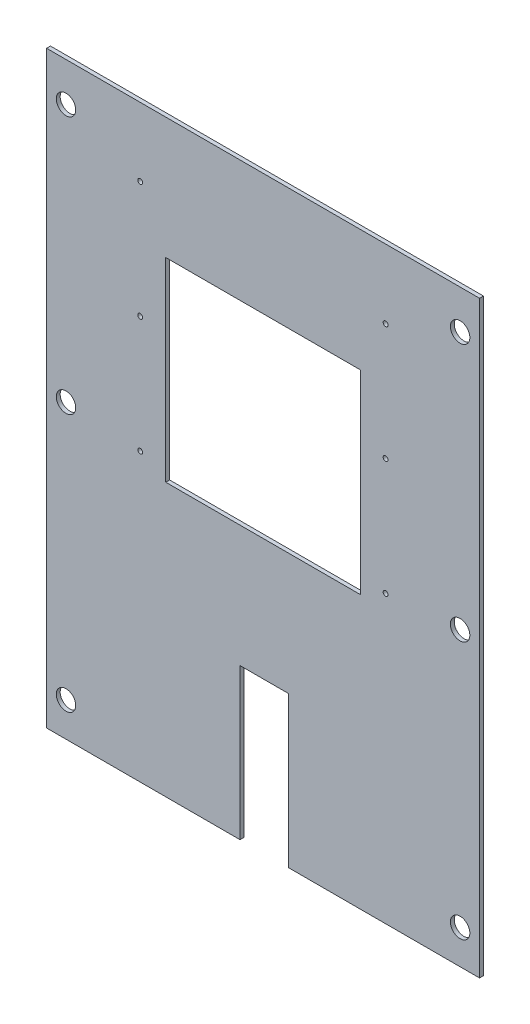
SolidWorks part; units mm, degrees
ref_plane "Front Plane" through (0, 0, 0) normal (0, 0, 1) x (1, 0, 0)
ref_plane "Top Plane" through (0, 0, 0) normal (0, 1, 0) x (1, 0, 0)
ref_plane "Right Plane" through (0, 0, 0) normal (1, 0, 0) x (0, 0, -1)
sketch "Sketch1" plane through (0, 0, 0) normal (0, 0, 1) x (1, 0, 0)
  line L0 (-141.2875, 166.6875) -> (-128.5875, 166.6875) construction
  line L1 (-141.2875, 192.0875) -> (141.2875, 192.0875)
  line L2 (-141.2875, 192.0875) -> (-141.2875, -192.0875)
  line L3 (-141.2875, -192.0875) -> (141.2875, -192.0875)
  line L4 (141.2875, 192.0875) -> (141.2875, -192.0875)
  line L5 (-141.2875, 192.0875) -> (141.2875, -192.0875) construction
  line L6 (-141.2875, -192.0875) -> (141.2875, 192.0875) construction
  line L7 (-128.5875, 166.6875) -> (-128.5875, 192.0875) construction
  line L8 (-15.0082, -192.0875) -> (16.7418, -192.0875)
  line L9 (-15.0082, -192.0875) -> (-15.0082, -93.6625)
  line L10 (-15.0082, -93.6625) -> (16.7418, -93.6625)
  line L11 (16.7418, -93.6625) -> (16.7418, -192.0875)
  line L18 (-128.5875, -1.5875) -> (-128.5875, -169.8625) construction
  line L19 (-63.5064, 112.7125) -> (63.4936, 112.7125)
  line L20 (-63.5064, 112.7125) -> (-63.5064, -14.2875)
  line L21 (-63.5064, -14.2875) -> (63.4936, -14.2875)
  line L22 (63.4936, 112.7125) -> (63.4936, -14.2875)
  line L23 (-63.5064, 112.7125) -> (63.4936, -14.2875) construction
  line L24 (-63.5064, -14.2875) -> (63.4936, 112.7125) construction
  line L25 (-128.5875, 166.6875) -> (-128.5875, -1.5875) construction
  circle A0 centre (-128.5875, 166.6875) radius 6.35
  circle A1 centre (-128.5875, -1.5875) radius 6.35
  circle A2 centre (-128.5875, -169.8625) radius 6.35
  circle A3 centre (128.5875, -1.5875) radius 6.35
  circle A4 centre (128.5875, 166.6875) radius 6.35
  circle A5 centre (128.5875, -169.8625) radius 6.35
  circle A6 centre (-80.1752, 147.3764) radius 1.5875
  circle A7 centre (-80.1752, 71.1764) radius 1.5875
  circle A8 centre (-80.1752, -5.0236) radius 1.5875
  circle A9 centre (79.9707, -5.3952) radius 1.5875
  circle A10 centre (79.9707, 70.8048) radius 1.5875
  circle A11 centre (79.9707, 147.0048) radius 1.5875
  point P0 (0, 0)
  point P20 (-0.0064, 49.2125)
  dimension "D1" = 16.6687
extrude "Boss-Extrude1" add sketch "Sketch1" along normal blind 2.54 contours L10 L11 L3 L4 L1 L2 L9 A4 L19 L22 L21 L20 A0 A1 A2 A3 A5
